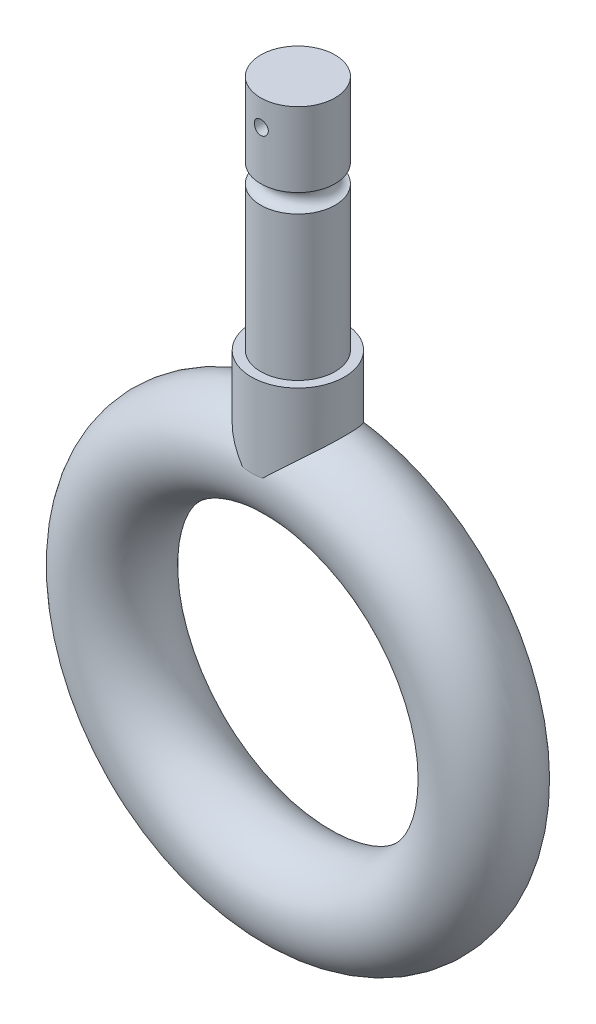
SolidWorks part; units mm, degrees
ref_plane "Ön Düzlem" through (0, 0, 0) normal (0, 0, 1) x (1, 0, 0)
ref_plane "Üst Düzlem" through (0, 0, 0) normal (0, 1, 0) x (1, 0, 0)
ref_plane "Sağ Düzlem" through (0, 0, 0) normal (1, 0, 0) x (0, 0, -1)
sketch "Çizim1" plane through (0, 0, 0) normal (1, 0, 0) x (0, 0, -1)
  line L0 (-15.2009, 0) -> (18.288, 0) construction
  circle A0 centre (0, 40) radius 10
revolve "Döndür1" add sketch "Çizim1" angle 360 about L0
sketch "Çizim2" plane through (0, 0, 0) normal (0, 0, 1) x (1, 0, 0)
  line L0 (0, 42.1014) -> (0, 111)
  line L1 (0, 111) -> (8, 111)
  line L2 (8, 111) -> (8, 60)
  line L3 (8, 60) -> (10, 60)
  line L4 (10, 60) -> (10, 42.1014)
  line L6 (0, 42.1014) -> (10, 42.1014)
  dimension "D1" = 51
  dimension "D2" = 8
  dimension "D3" = 10
revolve "Döndür2" add sketch "Çizim2" angle 360 about L0
cosmetic thread "Kozmetik Diş Açma1"
sketch "Çizim3" plane through (0, 0, 0) normal (0, 0, 1) x (1, 0, 0)
  line L0 (0, 111) -> (0, 105.5) construction
  line L1 (8, 111) -> (-8, 111) construction
  circle A0 centre (0, 105.5) radius 1.5
extrude "Kes-Ekstrüzyon1" cut sketch "Çizim3" against normal mid plane 30
sketch "Çizim4" plane through (0, 0, 0) normal (0, 0, 1) x (1, 0, 0)
  line L0 (8, 111) -> (8, 93) construction
  line L1 (8, 60) -> (8, 111) construction
  line L2 (-8, 111) -> (-8, 93) construction
  line L3 (-8, 111) -> (-8, 60) construction
  line L4 (0, 111) -> (0, 78.2179) construction
  line L5 (8, 111) -> (-8, 111) construction
  circle A0 centre (-8, 93) radius 2
revolve "Kes-Döndür1" cut sketch "Çizim4" angle 360 about L4
